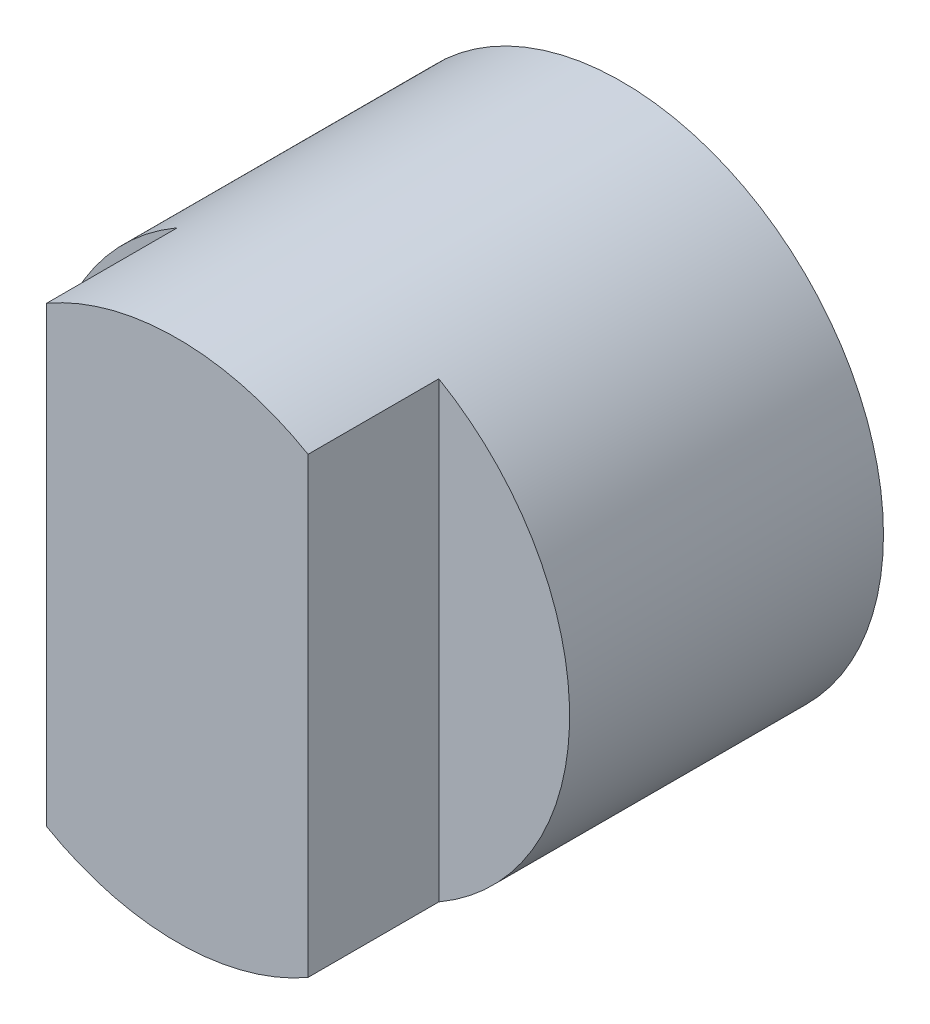
SolidWorks part; units mm, degrees
ref_plane "Plano frontal" through (0, 0, 0) normal (0, 0, 1) x (1, 0, 0)
ref_plane "Plano superior" through (0, 0, 0) normal (0, 1, 0) x (1, 0, 0)
ref_plane "Plano direito" through (0, 0, 0) normal (1, 0, 0) x (0, 0, -1)
sketch "Esboço1" plane through (0, 0, 0) normal (0, 0, 1) x (1, 0, 0)
  circle A0 centre (0, 0) radius 10
  dimension "D1" = 20
extrude "Ressalto-extrusão1" add sketch "Esboço1" along normal blind 17
sketch "Esboço2" plane through (0, 0, 17) normal (0, 0, 1) x (1, 0, 0)
  line L2 (-5, 8.6603) -> (-5, -8.6603)
  line L4 (5, 8.6603) -> (5, -8.6603)
  circle A0 centre (0, 0) radius 10 construction
  arc A1 (5, -8.6603) -> (5, 8.6603) centre (0, 0) ccw
  arc A2 (-5, 8.6603) -> (-5, -8.6603) centre (0, 0) ccw
  dimension "D1" = 5
  dimension "D2" = 5
extrude "Corte-extrusão1" cut sketch "Esboço2" against normal blind 5
sketch "Esboço3" plane through (0, 0, 0) normal (0, 0, -1) x (-1, 0, 0)
  line L0 (0, 3.175) -> (0, -2.725) construction
  line L1 (0, -2.725) -> (1.6294, -2.725)
  line L4 (-1.6294, -2.725) -> (0, -2.725)
  arc A0 (1.6294, -2.725) -> (-1.6294, -2.725) centre (0, 0) ccw
  dimension "D1" = 6.35
  dimension "D2" = 5.9
extrude "Corte-extrusão2" cut sketch "Esboço3" against normal blind 15
sketch "Esboço4" plane through (0, -2.725, 0) normal (0, 1, 0) x (1, 0, 0)
  line L0 (0, -15) -> (0, 0) construction
  line L1 (1.6294, -15) -> (-1.6294, -15) construction
  line L2 (1.6294, 0) -> (-1.6294, 0) construction
  circle A1 centre (0, -7) radius 1.5
  dimension "D1" = 3
  dimension "D2" = 7
extrude "Corte-extrusão3" cut sketch "Esboço4" against normal up to next
